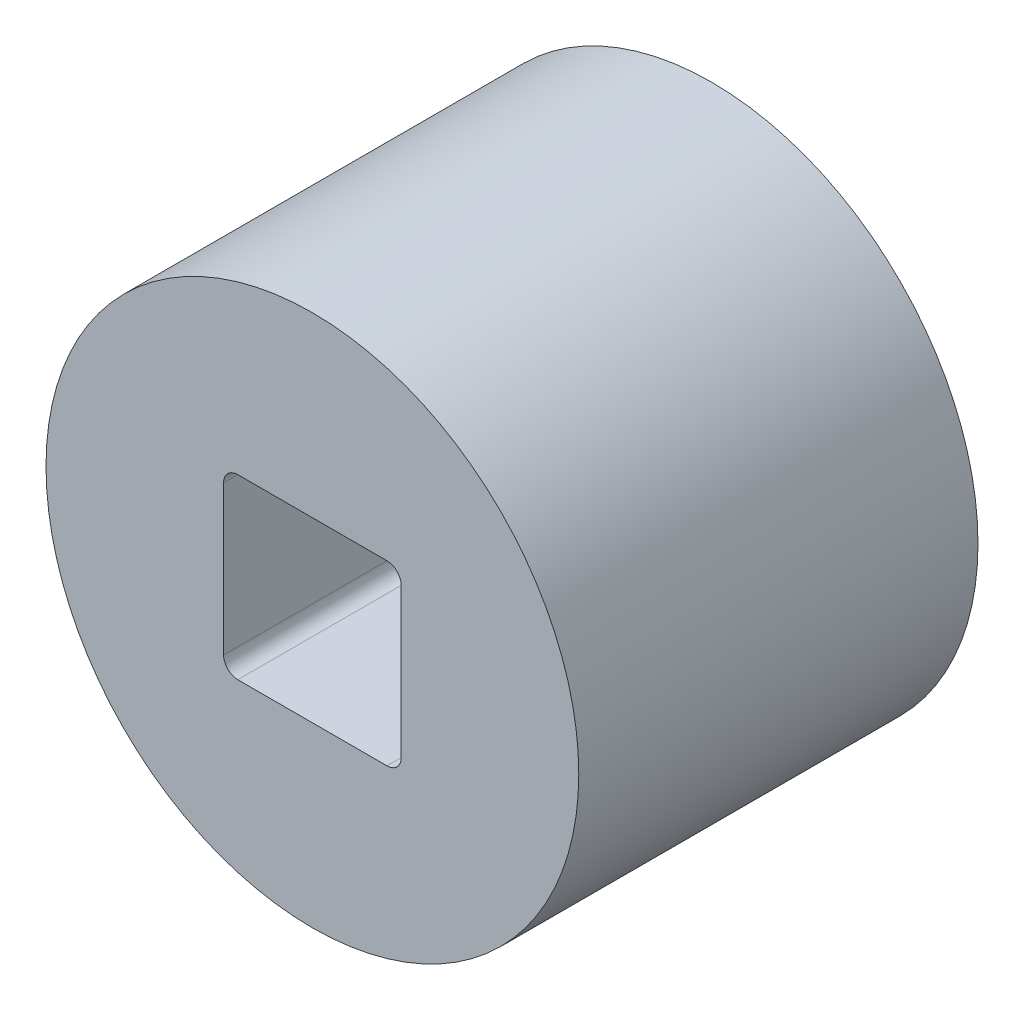
SolidWorks part; units mm, degrees
ref_plane "Front Plane" through (0, 0, 0) normal (0, 0, 1) x (1, 0, 0)
ref_plane "Top Plane" through (0, 0, 0) normal (0, 1, 0) x (1, 0, 0)
ref_plane "Right Plane" through (0, 0, 0) normal (1, 0, 0) x (0, 0, -1)
sketch "Sketch1" plane through (0, 0, 0) normal (0, 0, 1) x (1, 0, 0)
  line L1 (1.3335, 1.5875) -> (-1.3335, 1.5875)
  line L2 (1.5875, 1.3335) -> (1.5875, -1.3335)
  line L3 (1.3335, -1.5875) -> (-1.3335, -1.5875)
  line L4 (-1.5875, 1.3335) -> (-1.5875, -1.3335)
  line L5 (1.5875, 1.5875) -> (-1.5875, -1.5875) construction
  line L6 (1.5875, -1.5875) -> (-1.5875, 1.5875) construction
  circle A0 centre (0, 0) radius 4.7625
  arc A1 (-1.5875, -1.3335) -> (-1.3335, -1.5875) centre (-1.3335, -1.3335) ccw
  arc A2 (1.3335, -1.5875) -> (1.5875, -1.3335) centre (1.3335, -1.3335) ccw
  arc A3 (1.5875, 1.3335) -> (1.3335, 1.5875) centre (1.3335, 1.3335) ccw
  arc A4 (-1.5875, 1.3335) -> (-1.3335, 1.5875) centre (-1.3335, 1.3335) cw
  dimension "D1" = 9.525
  dimension "D3" = 0.254
  dimension "D2" = 3.175
extrude "Boss-Extrude1" add sketch "Sketch1" along normal blind 7.1374
